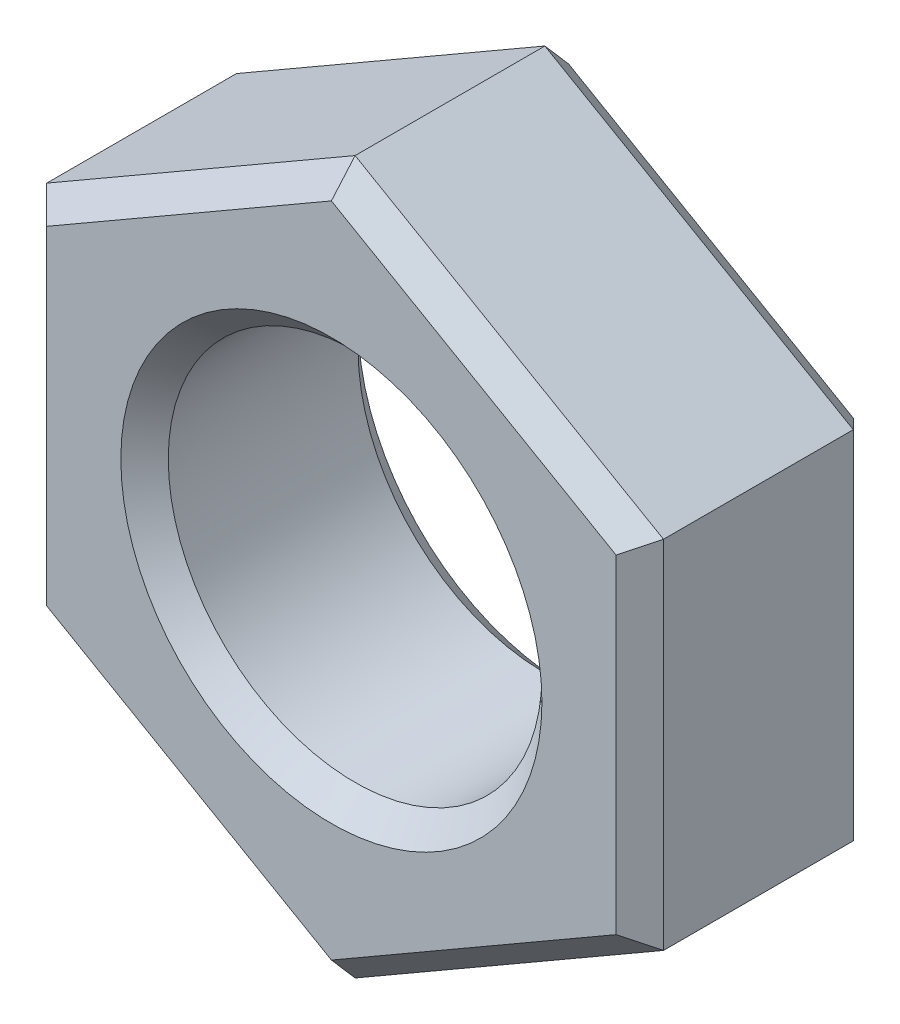
SolidWorks part; units mm, degrees
ref_plane "Front" through (0, 0, 0) normal (0, 0, 1) x (1, 0, 0)
ref_plane "Top" through (0, 0, 0) normal (0, 1, 0) x (1, 0, 0)
ref_plane "Right" through (0, 0, 0) normal (1, 0, 0) x (0, 0, -1)
sketch "Sketch1" plane through (0, 0, 0) normal (0, 0, 1) x (1, 0, 0)
  line L1 (2.6, -1.5011) -> (2.6, 1.5011)
  line L2 (2.6, 1.5011) -> (0, 3.0022)
  line L3 (0, 3.0022) -> (-2.6, 1.5011)
  line L4 (-2.6, 1.5011) -> (-2.6, -1.5011)
  line L5 (-2.6, -1.5011) -> (0, -3.0022)
  line L6 (0, -3.0022) -> (2.6, -1.5011)
  circle A0 centre (0, 0) radius 2.6 construction
  circle A1 centre (0, 0) radius 1.575
  point P10 (1.9872, 3.4419)
  point P11 (0, 3.8679)
  dimension "D1" = 3.15
  dimension "D2" = 5.2
extrude "Boss-Extrude1" add sketch "Sketch1" along normal mid plane 2
chamfer "Deburs" distance 0.2 angle 45 14 edges at (1.575, 0, -1) (2.6, 0, -1) (1.3, 2.2517, -1) (-1.3, 2.2517, -1) (-2.6, 0, -1) (-1.3, -2.2517, -1) (1.3, -2.2517, -1) (1.575, 0, 1) (-1.3, -2.2517, 1) (-2.6, 0, 1) (-1.3, 2.2517, 1) (1.3, 2.2517, 1) (2.6, 0, 1) (1.3, -2.2517, 1)
equation "\"D1@Sketch1\"=\"Hardware Clearance Hole Diameter@Box Assy.Assembly\""
equation "\"D2@Sketch1\"=\"Nut Trap Diameter@Box Assy.Assembly\"-0.3mm"
